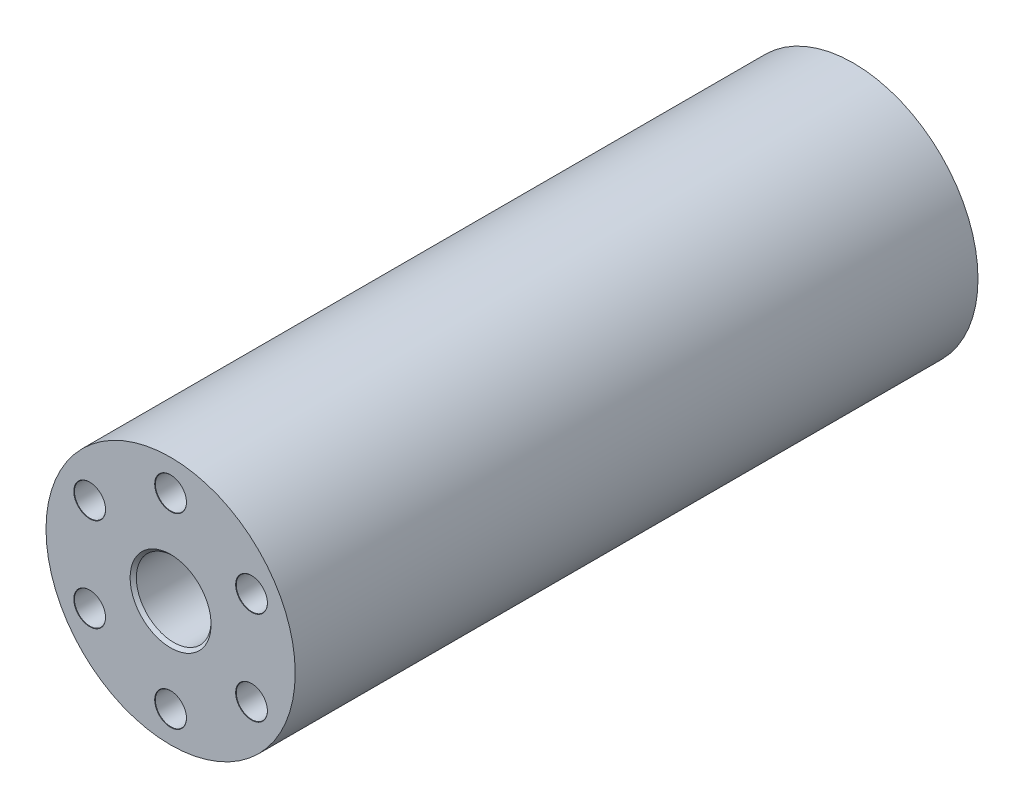
SolidWorks part; units mm, degrees
material "6061-T6 (SS)"
ref_plane "Front Plane" through (0, 0, 0) normal (0, 0, 1) x (1, 0, 0)
ref_plane "Top Plane" through (0, 0, 0) normal (0, 1, 0) x (1, 0, 0)
ref_plane "Right Plane" through (0, 0, 0) normal (1, 0, 0) x (0, 0, -1)
sketch "Sketch1" plane through (0, 0, 0) normal (0, 0, 1) x (1, 0, 0)
  circle A0 centre (0, 0) radius 10
  dimension "D1" = 20
extrude "Boss-Extrude1" add sketch "Sketch1" along normal blind 54.8
sketch "Sketch2" plane through (0, 0, 0) normal (0, 0, 1) x (1, 0, 0)
  point P0 (0, 0)
hole_wizard "Ø6.0mm Dowel Hole1" positions "Sketch2" profile "Sketch4" hole size "Ø6.0" standard "DIN" end condition through all
sketch "Sketch4" plane through (0, 0, 0) normal (1, 0, 0) x (0, 1, 0)
  line L0 (0, 0) -> (0, 54.8)
  line L1 (0, 54.8) -> (3.25, 54.8)
  line L2 (3, 54.55) -> (3, 0.25)
  line L3 (3, 0.25) -> (3.25, 0)
  line L5 (3.25, 0) -> (0, 0)
  line L6 (-3, 0.25) -> (-3.25, 0) construction
  line L7 (3.25, 54.8) -> (3, 54.55)
  line L8 (-3.25, 54.8) -> (-3, 54.55) construction
  line L11 (0, -6.35) -> (0, 107.95) construction
  dimension "Thru Hole Dia." = 6
  dimension "Thru Hole Depth" = 54.8
  dimension "Near C'Sink Dia." = 6.5
  dimension "Near C'Sink Angle" = 90
  dimension "Far C'Sink Dia." = 6.5
  dimension "Far C'Sink Angle" = 90
sketch "Sketch5" plane through (0, 0, 0) normal (0, 0, -1) x (-1, 0, 0)
  circle A0 centre (0, 0) radius 7
  point P6 (0, 7)
  point P10 (6.0622, -3.5)
  point P11 (-6.0622, -3.5)
  dimension "D1" = 14
  dimension "D2" = 3
hole_wizard "Tap Drill for M3 Tap1" positions "Sketch5" profile "Sketch6" hole size "M3" standard "DIN"
sketch "Sketch6" plane through (6.0622, -3.5, 0) normal (1, 0, 0) x (0, 1, 0)
  line L0 (0, 0) -> (0, 6.7511)
  line L1 (0, 6.7511) -> (1.25, 6)
  line L2 (1.25, 6) -> (1.25, 0.025)
  line L3 (1.25, 0.025) -> (1.275, 0)
  line L5 (1.275, 0) -> (0, 0)
  line L6 (-1.25, 0.025) -> (-1.275, 0) construction
  line L10 (0, 6.7511) -> (-1.25, 6) construction
  line L11 (0, -6.35) -> (0, 107.95) construction
  dimension "Hole Dia." = 2.5
  dimension "Hole Depth" = 6
  dimension "Near C'Sink Dia." = 2.55
  dimension "Near C'Sink Angle" = 90
  dimension "Drill Angle" = 118
sketch "Sketch7" plane through (0, 0, 54.8) normal (0, 0, 1) x (1, 0, 0)
  line L0 (0, 3) -> (0, 12) construction
  circle A0 centre (0, 0) radius 3 construction
  circle A2 centre (0, 0) radius 12 construction
  circle A4 centre (0, 0) radius 7.5 construction
  point P20 (0, 7.5)
  point P24 (6.4952, 3.75)
  point P25 (6.4952, -3.75)
  point P26 (0, -7.5)
  point P27 (-6.4952, -3.75)
  point P28 (-6.4952, 3.75)
  dimension "D1" = 15
  dimension "D2" = 6
hole_wizard "Tap Drill for M3 Tap2" positions "Sketch7" profile "Sketch9" hole size "M3" standard "DIN"
sketch "Sketch9" plane through (-6.4952, 3.75, 54.8) normal (1, 0, 0) x (0, -1, 0)
  line L0 (0, 0) -> (0, 6.7511)
  line L1 (0, 6.7511) -> (1.25, 6)
  line L2 (1.25, 6) -> (1.25, 0.025)
  line L3 (1.25, 0.025) -> (1.275, 0)
  line L5 (1.275, 0) -> (0, 0)
  line L6 (-1.25, 0.025) -> (-1.275, 0) construction
  line L10 (0, 6.7511) -> (-1.25, 6) construction
  line L11 (0, -6.35) -> (0, 107.95) construction
  dimension "Hole Dia." = 2.5
  dimension "Hole Depth" = 6
  dimension "Near C'Sink Dia." = 2.55
  dimension "Near C'Sink Angle" = 90
  dimension "Drill Angle" = 118
